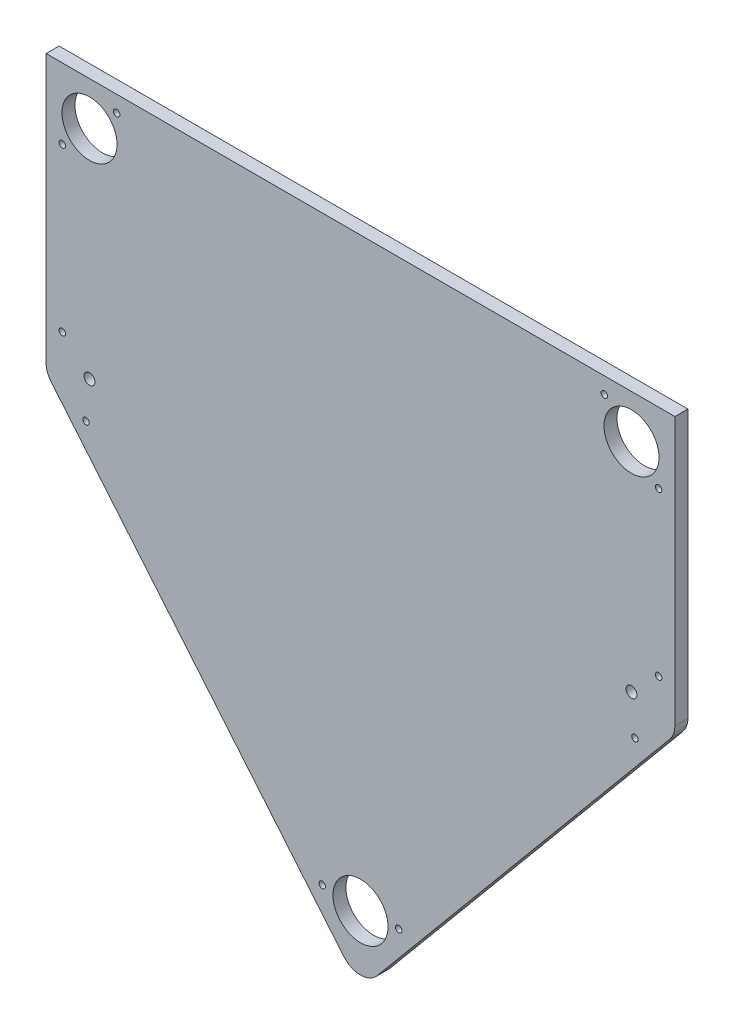
SolidWorks part; units mm, degrees
ref_plane "Front Plane" through (0, 0, 0) normal (0, 0, 1) x (1, 0, 0)
ref_plane "Top Plane" through (0, 0, 0) normal (0, 1, 0) x (1, 0, 0)
ref_plane "Right Plane" through (0, 0, 0) normal (1, 0, 0) x (0, 0, -1)
sketch "Sketch1" plane through (0, 0, 0) normal (0, 0, 1) x (1, 0, 0)
  line L0 (-125, 100) -> (125, 100) construction
  line L1 (-125, 0) -> (125, 0) construction
  line L2 (-137.5158, 87.4842) -> (-125, 100) construction
  line L3 (0, -150) -> (-125, 0) construction
  line L4 (0, -150) -> (-17.6273, -148.3975) construction
  line L5 (-126.6025, -17.6273) -> (-125, 0) construction
  line L6 (0, -150) -> (0, 100) construction
  line L7 (-145, 120) -> (145, 120)
  line L8 (145, 120) -> (145, -7.241)
  line L9 (145, -7.241) -> (0, -181.241)
  line L10 (0, -181.241) -> (-145, -7.241)
  line L11 (-145, -7.241) -> (-145, 120)
  circle A0 centre (-125, 100) radius 12.7
  circle A1 centre (125, 100) radius 12.7
  circle A2 centre (-125, 0) radius 2.5
  circle A3 centre (125, 0) radius 2.5
  circle A4 centre (0, -150) radius 12.7
  circle A5 centre (-137.5158, 87.4842) radius 1.5
  circle A6 centre (-112.4842, 112.5158) radius 1.5
  circle A7 centre (-137.5158, 12.5158) radius 1.5
  circle A8 centre (-126.6025, -17.6273) radius 1.5
  circle A9 centre (-17.6273, -148.3975) radius 1.5
  circle A10 centre (-125, 0) radius 12.7 construction
  circle A11 centre (125, 0) radius 12.7 construction
  circle A12 centre (-125, 0) radius 17.7 construction
  circle A13 centre (-125, 100) radius 17.7 construction
  circle A14 centre (0, -150) radius 17.7 construction
  circle A15 centre (17.6273, -148.3975) radius 1.5
  circle A16 centre (126.6025, -17.6273) radius 1.5
  circle A17 centre (137.5158, 12.5158) radius 1.5
  circle A18 centre (137.5158, 87.4842) radius 1.5
  circle A19 centre (112.4842, 112.5158) radius 1.5
  point P12 (0, 100)
  point P45 (0, 120)
  dimension "D1" = 25.4
  dimension "D2" = 5
  dimension "D5" = 3
  dimension "D4" = 100
  dimension "D6" = 5
  dimension "D7" = 135
  dimension "D8" = 45
  dimension "D9" = 250
  dimension "D10" = 45
  dimension "D11" = 20
  dimension "D12" = 20
  dimension "D13" = 20
  dimension "D14" = 20
  dimension "D15" = 20
  dimension "D3" = 150
extrude "Boss-Extrude1" add sketch "Sketch1" along normal blind 6
fillet "Fillet1" radius 10 3 edges at (-145, -7.241, 3) (145, -7.241, 3) (0, -181.241, 3)
equation "\"carbon_fiber_tube_diam\"= 1in"
equation "\"clip_tube_diam\"= 6mm"
equation "\"D1@Sketch1\"=\"carbon_fiber_tube_diam\""
